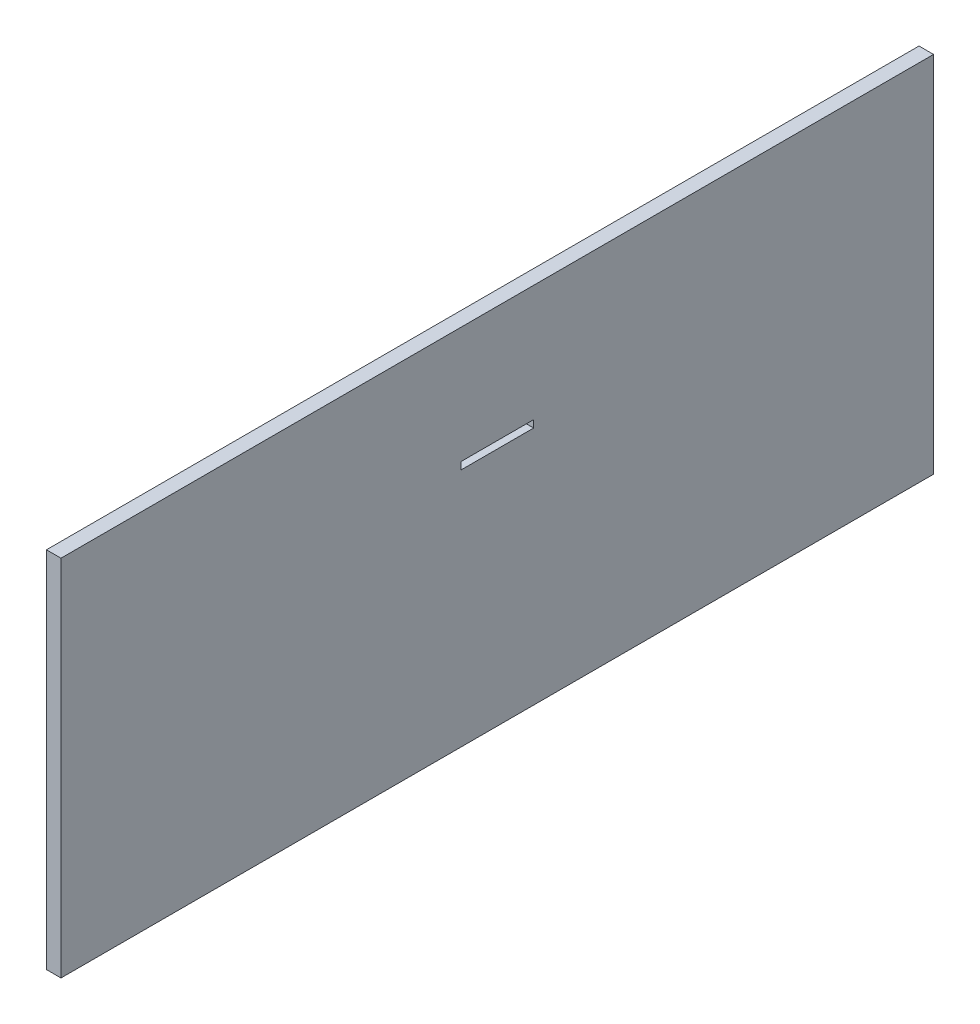
SolidWorks part; units mm, degrees
ref_plane "Front Plane" through (0, 0, 0) normal (0, 0, 1) x (1, 0, 0)
ref_plane "Top Plane" through (0, 0, 0) normal (0, 1, 0) x (1, 0, 0)
ref_plane "Right Plane" through (0, 0, 0) normal (1, 0, 0) x (0, 0, -1)
sketch "Sketch1" plane through (0, 0, 0) normal (1, 0, 0) x (0, 0, -1)
  line L0 (300, 7.2356) -> (300, -242.7644) construction
  line L1 (0, 7.2356) -> (600, 7.2356)
  line L2 (0, 7.2356) -> (0, -242.7644)
  line L3 (0, -242.7644) -> (600, -242.7644)
  line L4 (600, 7.2356) -> (600, -242.7644)
  line L10 (275, -72.7644) -> (325, -72.7644)
  line L11 (275, -72.7644) -> (275, -77.7644)
  line L12 (275, -77.7644) -> (325, -77.7644)
  line L13 (325, -72.7644) -> (325, -77.7644)
  dimension "D1" = 600
  dimension "D2" = 250
  dimension "D3" = 50
  dimension "D4" = 5
  dimension "D5" = 80
  dimension "D6" = 275
extrude "Boss-Extrude1" add sketch "Sketch1" along normal blind 10
